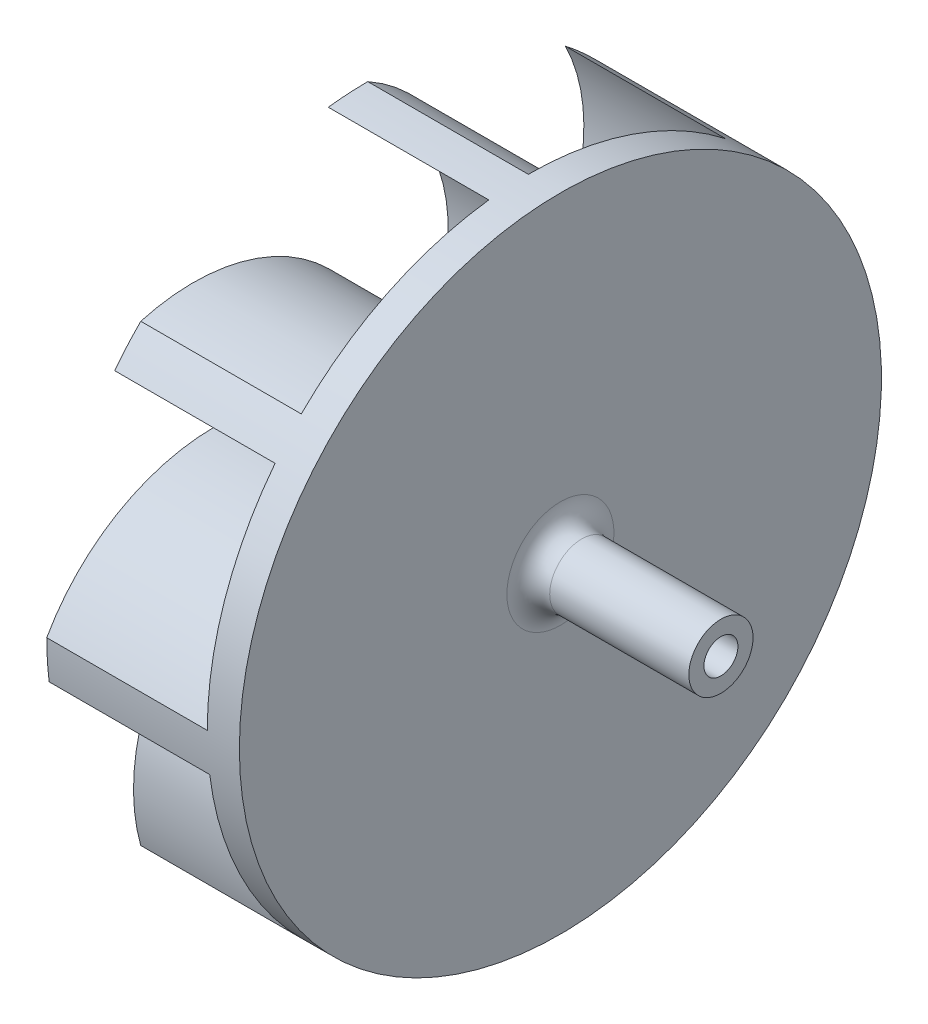
SolidWorks part; units mm, degrees
ref_plane "Front Plane" through (0, 0, 0) normal (0, 0, 1) x (1, 0, 0)
ref_plane "Top Plane" through (0, 0, 0) normal (0, 1, 0) x (1, 0, 0)
ref_plane "Right Plane" through (0, 0, 0) normal (1, 0, 0) x (0, 0, -1)
sketch "Sketch1" plane through (0, 0, 0) normal (0, 1, 0) x (1, 0, 0)
  line L0 (0, 0) -> (0, 30)
  line L1 (0, 30) -> (-3, 30)
  line L2 (-3, 30) -> (-3, 5)
  line L3 (-3, 5) -> (-8, 5)
  line L4 (-12, 1) -> (-12, 0)
  line L5 (-12, 0) -> (0, 0)
  arc A0 (-8, 5) -> (-12, 1) centre (-8, 1) ccw
  point P9 (-12, 5)
  dimension "D5" = 4
  dimension "D1" = 30
  dimension "D2" = 3
  dimension "D3" = 12
  dimension "D4" = 5
revolve "Revolve1" add sketch "Sketch1" angle 360 about L5
sketch "Sketch2" plane through (-3, 0, 0) normal (-1, 0, 0) x (0, 0, 1)
  line L0 (0, 0) -> (0, 30) construction
  line L1 (0, 0) -> (-8.1317, 8.1317) construction
  arc A0 (-6.7408, 9.3173) -> (-8.1317, 8.1317) centre (0, 0) ccw
  circle A1 centre (0, 0) radius 30 construction
  arc A2 (0, 30) -> (-8.1317, 8.1317) centre (8.7827, 14.2881) ccw
  arc A3 (3.6902, 29.7722) -> (-6.7408, 9.3173) centre (8.7827, 14.2881) ccw
  arc A4 (3.6902, 29.7722) -> (0, 30) centre (0, 0) ccw
  arc A5 (0.8295, 28.5161) -> (-6.5343, 8.7132) centre (8.7827, 14.2881) ccw construction
  dimension "D1" = 23
  dimension "D3" = 18
  dimension "D2" = 45
  dimension "D4" = 1.7
extrude "Boss-Extrude1" add sketch "Sketch2" along normal blind 15
pattern_circular "CirPattern1" count 8 over 360 about axis through (0, 0, 0) along (1, 0, 0) of "Boss-Extrude1"
sketch "Sketch4" plane through (0, 0, 0) normal (1, 0, 0) x (0, 0, -1)
  circle A0 centre (0, 0) radius 3
  dimension "D1" = 6
extrude "Boss-Extrude2" add sketch "Sketch4" along normal blind 15
sketch "Sketch5" plane through (15, 0, 0) normal (1, 0, 0) x (0, 0, -1)
  circle A0 centre (0, 0) radius 1.5877
  dimension "D1" = 3.1755
extrude "Cut-Extrude1" cut sketch "Sketch5" against normal blind 11.4
fillet "Fillet3" radius 2 1 edges at (0, 0, 3)
